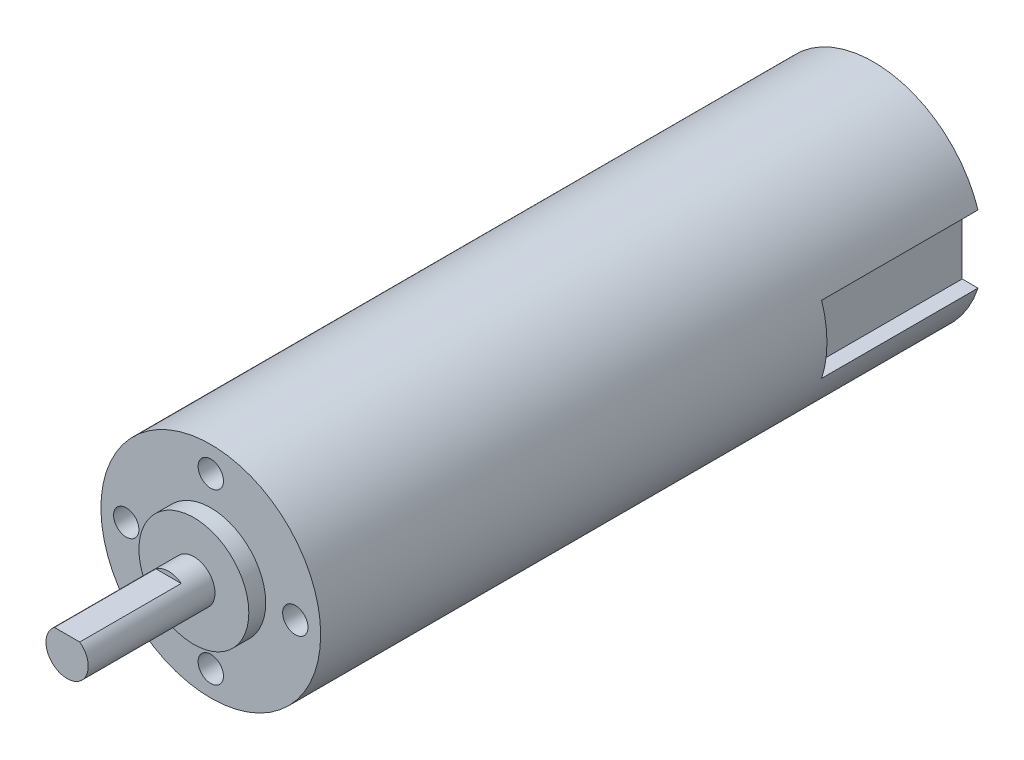
SolidWorks part; units mm, degrees
ref_plane "Plan de face" through (0, 0, 0) normal (0, 0, 1) x (1, 0, 0)
ref_plane "Plan de dessus" through (0, 0, 0) normal (0, 1, 0) x (1, 0, 0)
ref_plane "Plan de droite" through (0, 0, 0) normal (1, 0, 0) x (0, 0, -1)
sketch "Esquisse1" plane through (0, 0, 0) normal (0, 0, 1) x (1, 0, 0)
  circle A0 centre (0, 0) radius 13
  dimension "D1" = 26
extrude "Boss.-Extru.1" add sketch "Esquisse1" along normal blind 78.4
sketch "Esquisse2" plane through (0, 0, 78.4) normal (0, 0, 1) x (1, 0, 0)
  circle A0 centre (0, 0) radius 2.5
  dimension "D1" = 5
extrude "Boss.-Extru.2" add sketch "Esquisse2" along normal blind 17
sketch "Esquisse3" plane through (0, 0, 0) normal (0, 0, -1) x (-1, 0, 0)
  line L0 (-10.5, 0) -> (-10.5, 4)
  line L1 (10.5, 0) -> (13, 0) construction
  line L2 (-13, 0) -> (-10.5, 0) construction
  line L3 (-10.5, 4) -> (-12.3693, 4)
  line L4 (-10.5, 0) -> (-10.5, -4)
  line L5 (10.5, 0) -> (10.5, 4)
  line L6 (10.5, 4) -> (12.3693, 4)
  line L7 (10.5, 0) -> (10.5, -4)
  line L8 (10.5, -4) -> (12.365, -4.0133)
  line L9 (-10.5, -4) -> (-12.3693, -4)
  circle A0 centre (0, 0) radius 13 construction
  arc A1 (-12.3693, 4) -> (-12.3693, -4) centre (0, 0) ccw
  arc A2 (12.3693, 4) -> (12.365, -4.0133) centre (0, 0) cw
extrude "Enlèv. mat.-Extru.1" cut sketch "Esquisse3" against normal blind 18.5
sketch "Esquisse4" plane through (0, 0, 78.4) normal (0, 0, 1) x (1, 0, 0)
  circle A0 centre (0, 0) radius 6.5
  circle A1 centre (0, 0) radius 2.5
extrude "Boss.-Extru.3" add sketch "Esquisse4" along normal blind 2
sketch "Esquisse5" plane through (0, 0, 78.4) normal (0, 0, 1) x (1, 0, 0)
  line L0 (0, 0) -> (10, 0) construction
  line L1 (0, 0) -> (0, 10) construction
  line L2 (0, 0) -> (-10, 0) construction
  line L3 (0, 0) -> (0, -10) construction
  circle A0 centre (0, 10) radius 1.5
  circle A1 centre (-10, 0) radius 1.5
  circle A2 centre (0, -10) radius 1.5
  circle A3 centre (10, 0) radius 1.5
  dimension "D1" = 3
extrude "Enlèv. mat.-Extru.2" cut sketch "Esquisse5" against normal blind 4
sketch "Esquisse6" plane through (0, 0, 95.4) normal (0, 0, 1) x (1, 0, 0)
  line L0 (0, -2.5) -> (0, 2) construction
  line L1 (0, 2) -> (1.5, 2)
  line L2 (0, 2) -> (-1.5, 2)
  circle A2 centre (0, 0) radius 2.5 construction
  circle A3 centre (0, 0) radius 2.5 construction
  arc A4 (-1.5, 2) -> (1.5, 2) centre (0, 0) cw
extrude "Enlèv. mat.-Extru.3" cut sketch "Esquisse6" against normal blind 12
